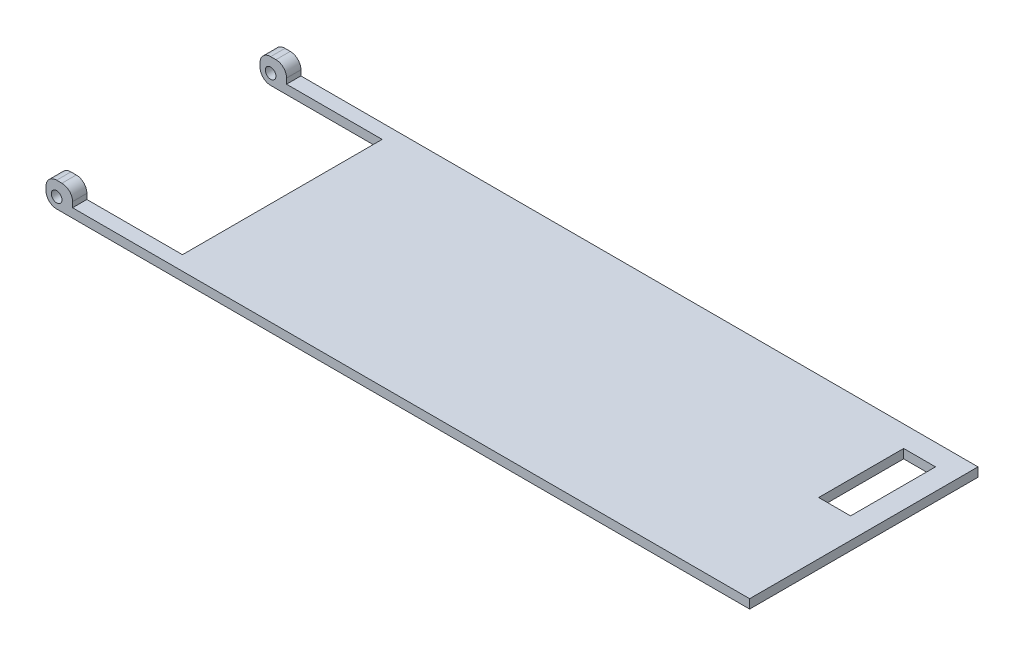
SolidWorks part; units mm, degrees
ref_plane "Front Plane" through (0, 0, 0) normal (0, 0, 1) x (1, 0, 0)
ref_plane "Top Plane" through (0, 0, 0) normal (0, 1, 0) x (1, 0, 0)
ref_plane "Right Plane" through (0, 0, 0) normal (1, 0, 0) x (0, 0, -1)
sketch "Sketch1" plane through (0, 0, 0) normal (0, 1, 0) x (1, 0, 0)
  line L1 (-66.25, -21.5) -> (66.25, -21.5)
  line L2 (-66.25, -21.5) -> (-66.25, 21.5)
  line L3 (-66.25, 21.5) -> (66.25, 21.5)
  line L4 (66.25, -21.5) -> (66.25, 21.5)
  line L5 (-66.25, -21.5) -> (66.25, 21.5) construction
  line L6 (-66.25, 21.5) -> (66.25, -21.5) construction
  point P0 (0, 0)
  dimension "D1" = 132.5
  dimension "D2" = 43
extrude "Boss-Extrude1" add sketch "Sketch1" along normal blind 1.7
sketch "Sketch2" plane through (0, 1.7, 0) normal (0, 1, 0) x (1, 0, 0)
  line L0 (-66.25, 21.5) -> (-66.25, -21.5) construction
  line L1 (-66.25, -18.8) -> (-43.25, -18.8)
  line L2 (-66.25, -18.8) -> (-66.25, 18.8)
  line L3 (-66.25, 18.8) -> (-43.25, 18.8)
  line L4 (-43.25, -18.8) -> (-43.25, 18.8)
  line L5 (-66.25, -21.5) -> (66.25, -21.5) construction
  line L6 (66.25, 21.5) -> (-66.25, 21.5) construction
  dimension "D1" = 2.7
  dimension "D2" = 2.7
  dimension "D3" = 23
extrude "Cut-Extrude1" cut sketch "Sketch2" against normal up to vertex (1.7 mm away)
sketch "Sketch4" plane through (0, 1.7, 0) normal (0, 1, 0) x (1, 0, 0)
  line L0 (-66.25, -21.5) -> (66.25, -21.5) construction
  line L1 (-66.25, -18.8) -> (-61.25, -18.8)
  line L2 (-66.25, -18.8) -> (-66.25, -21.5)
  line L3 (-66.25, -21.5) -> (-61.25, -21.5)
  line L4 (-61.25, -18.8) -> (-61.25, -21.5)
  dimension "D1" = 5
extrude "Boss-Extrude2" add sketch "Sketch4" along normal blind 3
sketch "Sketch5" plane through (0, 0, 21.5) normal (0, 0, 1) x (1, 0, 0)
  line L0 (-66.25, 0) -> (66.25, 0) construction
  line L1 (-66.25, 4.7) -> (-66.25, 0) construction
  circle A0 centre (-64.25, 2) radius 1
  dimension "D3" = 2
  dimension "D1" = 2
  dimension "D2" = 2
extrude "Cut-Extrude2" cut sketch "Sketch5" against normal up to vertex (2.7 mm away) contours A0
fillet "Fillet1" radius 2 3 edges at (-66.25, 0, 20.15) (-66.25, 4.7, 20.15) (-61.25, 4.7, 20.15)
ref_plane "Plane1" through (0, 0, 0) normal (0, 0, 1) x (1, 0, 0)
mirror "Mirror2" about plane through (0, 0, 0) normal (0, 0, 1) of "Boss-Extrude2", "Cut-Extrude2", "Fillet1"
sketch "Sketch10" plane through (0, 1.7, 0) normal (0, 1, 0) x (1, 0, 0)
  line L0 (66.25, -21.5) -> (66.25, 21.5) construction
  line L1 (56.25, 1.5) -> (62.25, 1.5)
  line L2 (56.25, 1.5) -> (56.25, 17.5)
  line L3 (56.25, 17.5) -> (62.25, 17.5)
  line L4 (62.25, 1.5) -> (62.25, 17.5)
  line L5 (56.25, 1.5) -> (62.25, 17.5) construction
  line L6 (56.25, 17.5) -> (62.25, 1.5) construction
  line L7 (66.25, 21.5) -> (-61.25, 21.5) construction
  point P0 (59.25, 9.5)
  dimension "D1" = 4
  dimension "D2" = 6
  dimension "D3" = 4
  dimension "D4" = 16
extrude "Cut-Extrude3" cut sketch "Sketch10" against normal up to vertex (1.7 mm away) up to point (66.25, 0, -21.5)
